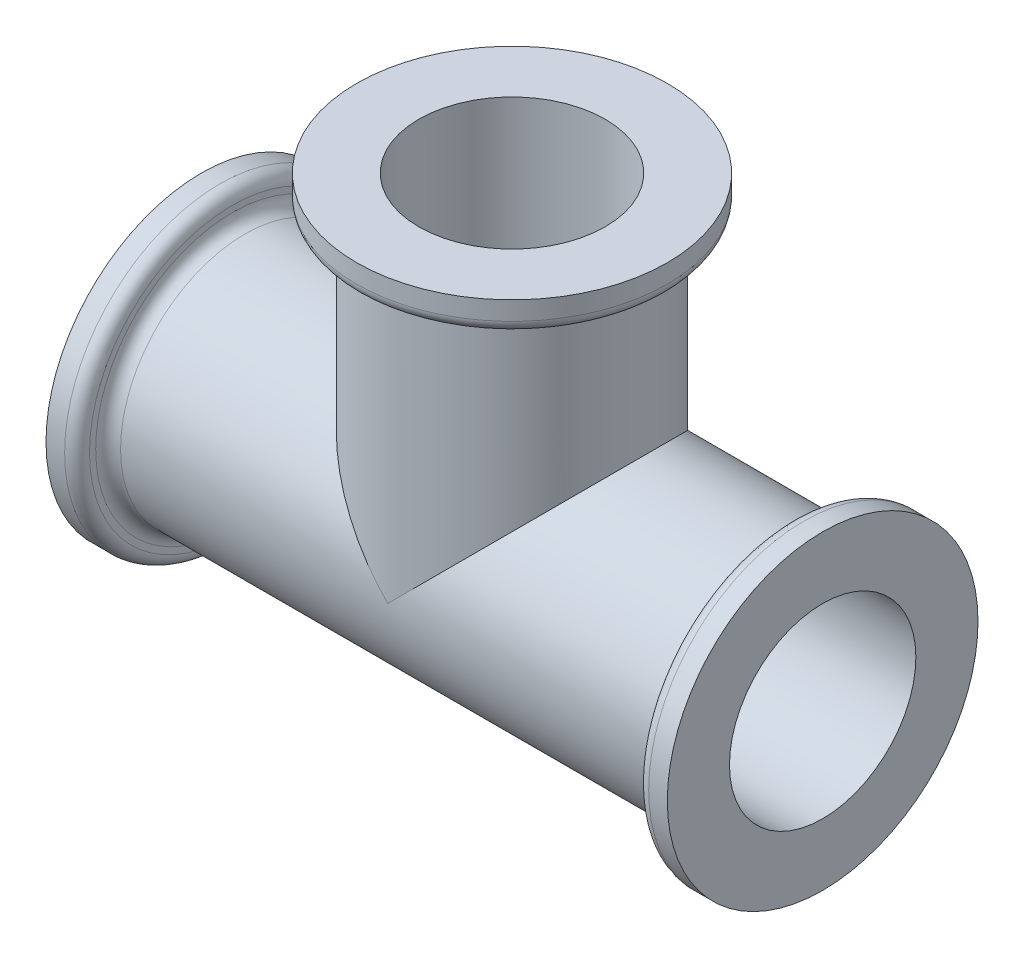
SolidWorks part; units mm, degrees
ref_plane "Front Plane" through (0, 0, 0) normal (0, 0, 1) x (1, 0, 0)
ref_plane "Top Plane" through (0, 0, 0) normal (0, 1, 0) x (1, 0, 0)
ref_plane "Right Plane" through (0, 0, 0) normal (1, 0, 0) x (0, 0, -1)
sketch "Sketch1" plane through (0, 0, 0) normal (0, 0, 1) x (1, 0, 0)
  line L0 (-25, 7.5) -> (-25, 12.5)
  line L1 (-25, 12.5) -> (-22.5, 12.5)
  line L2 (-22.5, 12.5) -> (-22.5, 10)
  line L3 (0, -55) -> (0, 55) construction
  line L4 (22.5, 12.5) -> (22.5, 10)
  line L5 (25, 12.5) -> (22.5, 12.5)
  line L6 (25, 7.5) -> (25, 12.5)
  line L7 (-22.5, 10) -> (22.5, 10)
  line L8 (25, 7.5) -> (-25, 7.5)
  line L9 (0, 0) -> (67.3935, 0) construction
  dimension "D1" = 7.5
  dimension "D2" = 50
  dimension "D3" = 12.5
  dimension "D4" = 2.5
  dimension "D5" = 2.5
revolve "Revolve1" add sketch "Sketch1" angle 360 about L9
ref_plane "Plane1" through (0, 25, 0) normal (0, 1, 0) x (1, 0, 0)
sketch "Sketch2" plane through (0, 25, 0) normal (0, 1, 0) x (1, 0, 0)
  circle A0 centre (0, 0) radius 10
  dimension "D1" = 20
extrude "Boss-Extrude1" add sketch "Sketch2" against normal up to next
sketch "Sketch3" plane through (0, 25, 0) normal (0, 1, 0) x (1, 0, 0)
  circle A0 centre (0, 0) radius 12.5
  dimension "D1" = 25
extrude "Boss-Extrude2" add sketch "Sketch3" against normal blind 2.5
sketch "Sketch6" plane through (0, 25, 0) normal (0, 1, 0) x (1, 0, 0)
  circle A0 centre (0, 0) radius 7.5
  dimension "D1" = 15
extrude "Cut-Extrude1" cut sketch "Sketch6" against normal up to next
fillet "Fillet1" radius 1 3 edges at (0, 22.5, 10) (22.5, 0, 10) (-22.5, 0, 10)
fillet "Fillet2" radius 1 3 edges at (0, 22.5, 12.5) (22.5, 0, 12.5) (-22.5, 0, 12.5)
